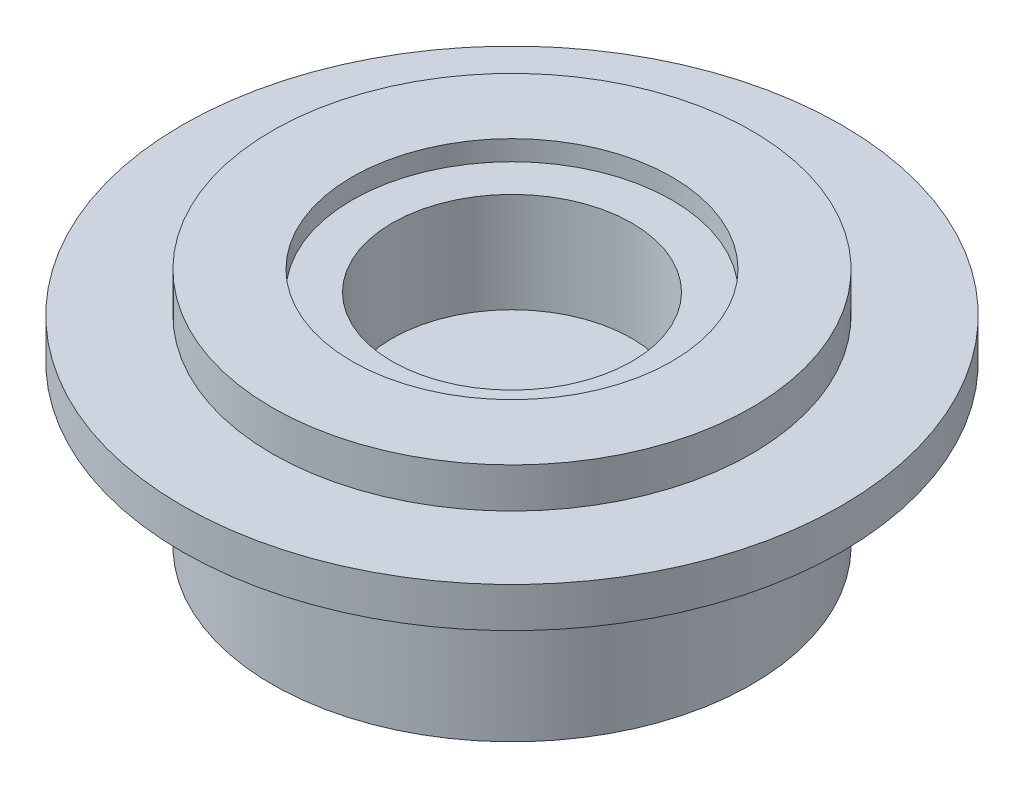
SolidWorks part; units mm, degrees
material "Brass"
ref_plane "Ön Düzlem" through (0, 0, 0) normal (0, 0, 1) x (1, 0, 0)
ref_plane "Üst Düzlem" through (0, 0, 0) normal (0, 1, 0) x (1, 0, 0)
ref_plane "Sağ Düzlem" through (0, 0, 0) normal (1, 0, 0) x (0, 0, -1)
sketch "Sketch2" plane through (0, 0, 0) normal (0, 1, 0) x (1, 0, 0)
  circle A0 centre (0, 0) radius 16.5
  dimension "D1" = 33
extrude "Boss-Extrude1" add sketch "Sketch2" along normal mid plane 2
sketch "Sketch3" plane through (0, -1, 0) normal (0, -1, 0) x (1, 0, 0)
  circle A0 centre (0, 0) radius 12
  dimension "D1" = 24
extrude "Boss-Extrude2" add sketch "Sketch3" along normal blind 8
sketch "Sketch4" plane through (0, 1, 0) normal (0, 1, 0) x (1, 0, 0)
  circle A0 centre (0, 0) radius 12
  dimension "D1" = 24
extrude "Boss-Extrude3" add sketch "Sketch4" along normal blind 2
sketch "Sketch5" plane through (0, 3, 0) normal (0, 1, 0) x (1, 0, 0)
  circle A0 centre (0, 0) radius 6
  dimension "D1" = 12
extrude "Cut-Extrude1" cut sketch "Sketch5" against normal blind 6
sketch "Sketch6" plane through (0, 3, 0) normal (0, 1, 0) x (1, 0, 0)
  circle A0 centre (0, 0) radius 8
  dimension "D1" = 16
extrude "Cut-Extrude2" cut sketch "Sketch6" against normal blind 1
